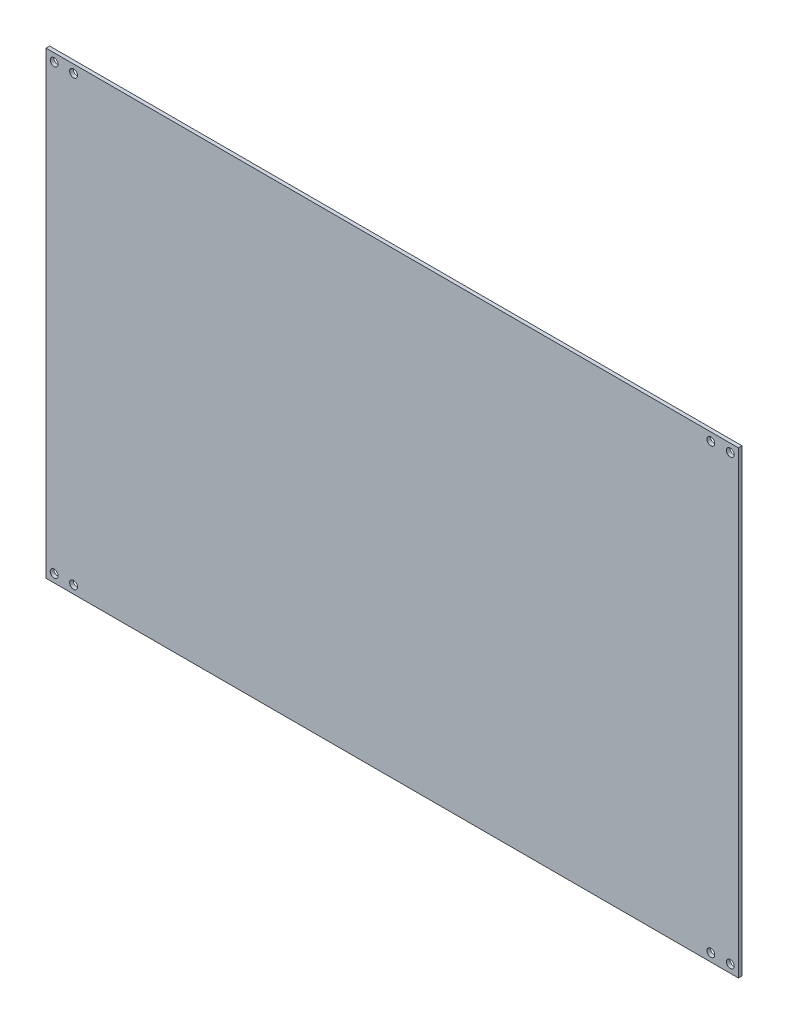
SolidWorks part; units mm, degrees
ref_plane "Alzado" through (0, 0, 0) normal (0, 0, 1) x (1, 0, 0)
ref_plane "Planta" through (0, 0, 0) normal (0, 1, 0) x (1, 0, 0)
ref_plane "Vista lateral" through (0, 0, 0) normal (1, 0, 0) x (0, 0, -1)
sketch "Croquis1" plane through (0, 0, 0) normal (0, 0, 1) x (1, 0, 0)
  line L0 (0, -55) -> (0, 55) construction
  line L1 (-133.6, 88.6) -> (133.6, 88.6)
  line L2 (-133.6, 88.6) -> (-133.6, -88.6)
  line L3 (-133.6, -88.6) -> (133.6, -88.6)
  line L4 (133.6, 88.6) -> (133.6, -88.6)
  line L5 (55, 0) -> (-55, 0) construction
  point P4 (-133.6, 0)
  point P5 (0, 88.6)
  dimension "D1" = 267.2
  dimension "D2" = 177.2
extrude "Saliente-Extruir1" add sketch "Croquis1" along normal mid plane 1.4
sketch "Croquis2" plane through (0, 0, 0.7) normal (0, 0, 1) x (1, 0, 0)
  line L0 (-133.6, 88.6) -> (-133.6, -88.6) construction
  line L1 (133.6, 88.6) -> (-133.6, 88.6) construction
  line L2 (133.6, -88.6) -> (133.6, 88.6) construction
  line L3 (133.6, 85.475) -> (-133.6, 85.475) construction
  line L4 (-133.6, -88.6) -> (133.6, -88.6) construction
  line L5 (-133.6, -85.475) -> (133.6, -85.475) construction
  circle A0 centre (-130.475, 85.475) radius 1.5
  circle A1 centre (-122.975, 85.475) radius 1.5
  circle A2 centre (-130.475, -85.475) radius 1.5
  circle A3 centre (-122.975, -85.475) radius 1.5
  circle A4 centre (130.475, -85.475) radius 1.5
  circle A5 centre (122.975, -85.475) radius 1.5
  circle A6 centre (130.475, 85.475) radius 1.5
  circle A7 centre (122.975, 85.475) radius 1.5
  point P0 (-133.6, 85.475)
  point P5 (133.6, 85.475)
  point P10 (-133.6, -85.475)
  point P11 (133.6, -85.475)
  point P16 (-130.475, -85.475)
  point P17 (-122.975, -85.475)
  point P18 (130.475, -85.475)
  point P19 (122.975, -85.475)
  point P20 (130.475, 85.475)
  point P21 (122.975, 85.475)
  point P22 (-130.475, 85.475)
  point P23 (-122.975, 85.475)
  dimension "D12" = 3.125
  dimension "D1" = 3.125
  dimension "D2" = 3.125
  dimension "D3" = 3.125
  dimension "D4" = 3.125
  dimension "D5" = 7.5
  dimension "D6" = 3.125
  dimension "D7" = 7.5
  dimension "D8" = 3.125
  dimension "D9" = 7.5
  dimension "D10" = 3.125
  dimension "D11" = 7.5
extrude "Cortar-Extruir1" cut sketch "Croquis2" against normal mid plane 31.4
